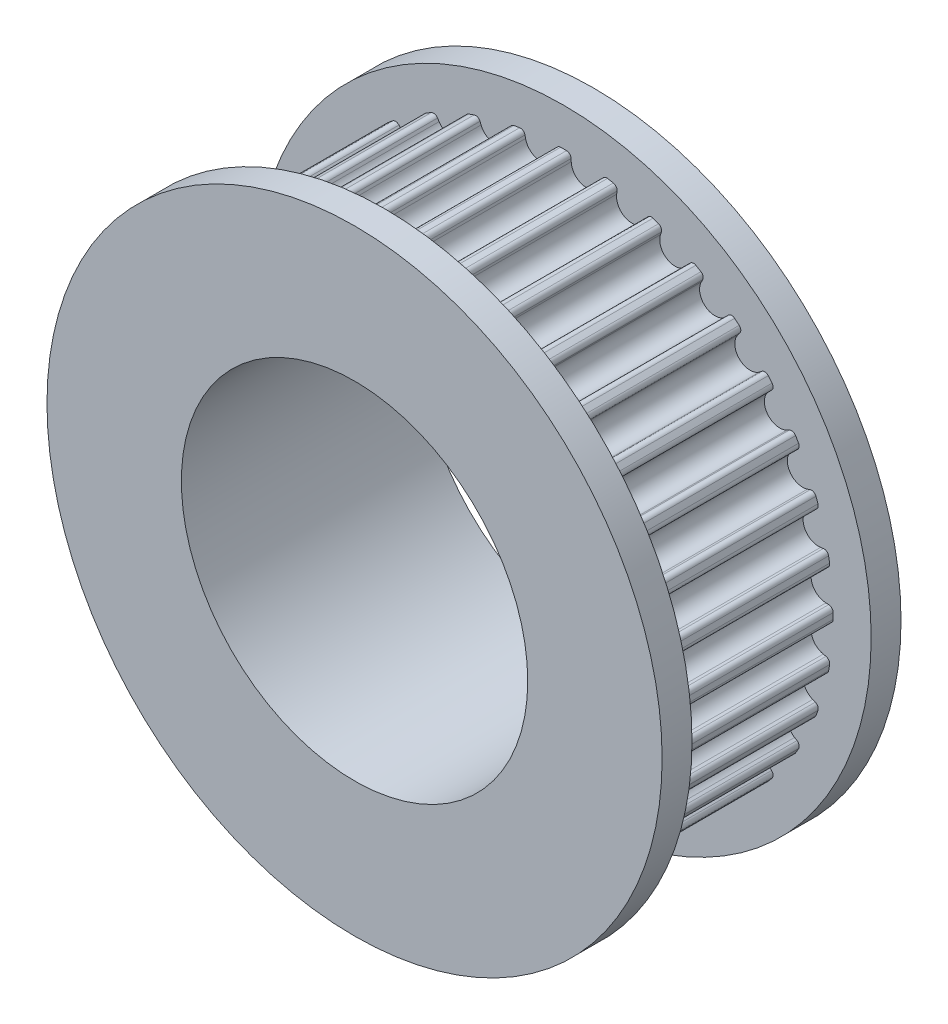
SolidWorks part; units mm, degrees
ref_plane "前视基准面" through (0, 0, 0) normal (0, 0, 1) x (1, 0, 0)
ref_plane "上视基准面" through (0, 0, 0) normal (0, 1, 0) x (1, 0, 0)
ref_plane "右视基准面" through (0, 0, 0) normal (1, 0, 0) x (0, 0, -1)
sketch "Sketch2" plane through (0, 0, 0) normal (0, 0, 1) x (1, 0, 0)
  circle A0 centre (0, 0) radius 45.15
  dimension "D1" = 90.3
extrude "Extrude1" add sketch "Sketch2" along normal mid plane 30
sketch "Sketch1" plane through (0, 0, 15) normal (0, 0, 1) x (1, 0, 0)
  line L0 (0, 0) -> (0, 45.835) construction
  line L1 (0, 0) -> (-3.9948, 45.6606) construction
  line L2 (-1.2656, 44.3946) -> (-1.2821, 43.9222)
  line L3 (-6.4627, 43.9399) -> (-6.3644, 43.4775)
  circle A0 centre (0, 0) radius 45.835 construction
  arc A1 (-0.4946, 45.1473) -> (-7.3526, 44.5473) centre (0, 0) ccw
  arc A2 (-6.3644, 43.4775) -> (-1.2821, 43.9222) centre (-3.8505, 44.0119) ccw
  arc A3 (-0.4946, 45.1473) -> (-1.2656, 44.3946) centre (-0.4861, 44.3673) ccw
  arc A4 (-7.3526, 44.5473) -> (-6.4627, 43.9399) centre (-7.2256, 43.7777) cw
  point P4 (45.6606, 3.9948)
  point P5 (44.2732, 11.863)
  point P6 (41.5406, 19.3707)
  point P7 (37.5458, 26.2899)
  point P8 (32.4102, 32.4102)
  point P9 (26.2899, 37.5458)
  point P10 (19.3707, 41.5406)
  point P11 (11.863, 44.2732)
  point P12 (3.9948, 45.6606)
  point P13 (-3.9948, 45.6606)
  point P14 (-11.863, 44.2732)
  point P15 (-19.3707, 41.5406)
  point P16 (-26.2899, 37.5458)
  point P17 (-32.4102, 32.4102)
  point P18 (-37.5458, 26.2899)
  point P19 (-41.5406, 19.3707)
  point P20 (-44.2732, 11.863)
  point P21 (-45.6606, 3.9948)
  point P22 (-45.6606, -3.9948)
  point P23 (-44.2732, -11.863)
  point P24 (-41.5406, -19.3707)
  point P25 (-37.5458, -26.2899)
  point P26 (-32.4102, -32.4102)
  point P27 (-26.2899, -37.5458)
  point P28 (-19.3707, -41.5406)
  point P29 (-11.863, -44.2732)
  point P30 (-3.9948, -45.6606)
  point P31 (3.9948, -45.6606)
  point P32 (11.863, -44.2732)
  point P33 (19.3707, -41.5406)
  point P34 (26.2899, -37.5458)
  point P35 (32.4102, -32.4102)
  point P36 (37.5458, -26.2899)
  point P37 (41.5406, -19.3707)
  point P38 (44.2732, -11.863)
  point P39 (45.6606, -3.9948)
  dimension "D1" = 91.67
  dimension "D2" = 90.3
  dimension "D3" = 5.14
  dimension "D4" = 3.54
  dimension "D5" = 1.56
  dimension "D6" = 7
extrude "Extrude2" cut sketch "Sketch1" against normal through all
pattern_circular "CirPattern1" count 36 over 360 about axis through (0, 0, 0) along (0, 0, 1) of "Extrude2"
sketch "Sketch3" plane through (0, 0, -15) normal (0, 0, -1) x (-1, 0, 0)
  circle A0 centre (0, 0) radius 51.5
  dimension "D1" = 103
extrude "Extrude3" add sketch "Sketch3" along normal blind 5
sketch "Sketch4" plane through (0, 0, 15) normal (0, 0, 1) x (1, 0, 0)
  circle A0 centre (0, 0) radius 51.5
  circle A1 centre (0, 0) radius 51.5 construction
extrude "Extrude4" add sketch "Sketch4" along normal blind 5
sketch "Sketch5" plane through (0, 0, 20) normal (0, 0, 1) x (1, 0, 0)
  circle A0 centre (0, 0) radius 29
  dimension "D1" = 58
extrude "Extrude5" cut sketch "Sketch5" against normal through all
